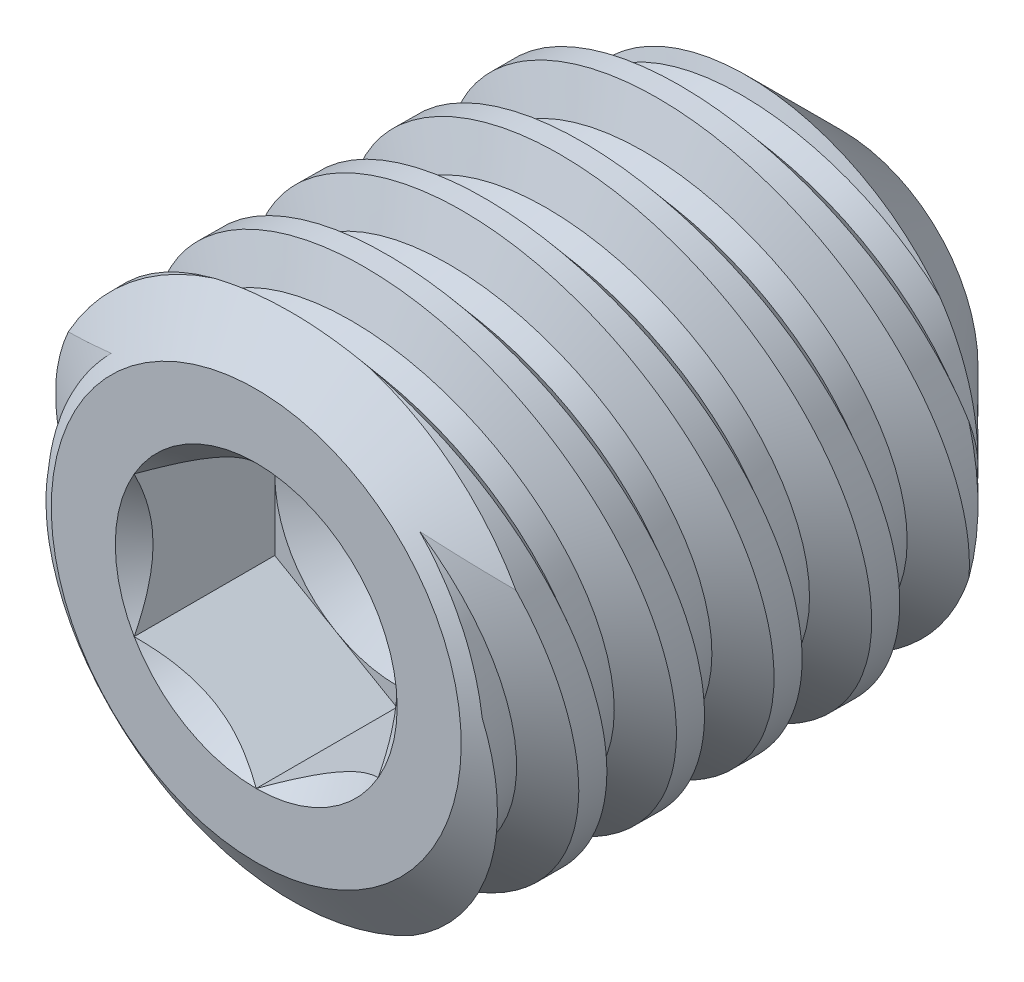
SolidWorks part; units mm, degrees
ref_plane "Front" through (0, 0, 0) normal (0, 0, 1) x (1, 0, 0)
ref_plane "Top" through (0, 0, 0) normal (0, 1, 0) x (1, 0, 0)
ref_plane "Right" through (0, 0, 0) normal (1, 0, 0) x (0, 0, -1)
sketch "Sketch22" plane through (0, 0, 0) normal (1, 0, 0) x (0, 0, -1)
  line L0 (-2.0493, 0) -> (-2.0493, 1.6662)
  line L1 (-2.0493, 1.6662) -> (-1.7576, 2.0828)
  line L2 (-1.7576, 2.0828) -> (1.7353, 2.0828)
  line L3 (1.7353, 2.0828) -> (2.7132, 1.1049)
  line L4 (2.7132, 1.1049) -> (2.0493, 0)
  line L5 (2.0493, 0) -> (-2.0493, 0)
  line L6 (2.0493, 0) -> (2.7132, 0) construction
  line L7 (2.7132, 0) -> (2.7132, 1.1049) construction
  line L8 (2.7132, -1.1049) -> (2.0493, 0) construction
  line L9 (-1.7576, -2.0828) -> (1.7353, -2.0828) construction
  dimension "Screw Dia" = 4.1656
  dimension "Length" = 4.7625
  dimension "D3" = 35
  dimension "Cup Point Dia" = 2.2098
  dimension "D5" = 118
  dimension "D6" = 45
  dimension "D7" = 3.3325
revolve "Revolve1" add sketch "Sketch22" angle 360 about L6
sketch "Sketch6" plane through (0, 0, 0) normal (1, 0, 0) x (0, 0, -1)
  line L0 (0.487, 2.0828) -> (1.2808, -2.0828) construction
  line L1 (-1.7576, 2.0828) -> (1.7353, 2.0828) construction
  line L2 (-1.7576, -2.0828) -> (1.7353, -2.0828) construction
  line L3 (0.487, 2.0828) -> (0.5845, 2.1014) construction
  line L4 (1.1035, 1.7629) -> (0.9086, 1.7258)
  line L5 (0.9086, 1.7258) -> (0.5845, 2.1014)
  line L6 (1.1035, 1.7629) -> (1.2667, 2.2314)
  line L7 (1.2667, 2.2314) -> (0.5845, 2.1014)
  line L8 (0.9415, 2.0828) -> (1.7353, -2.0828) construction
  line L9 (2.1898, 0.1622) -> (0.487, -0.1622) construction
  line L10 (0.9256, 2.1664) -> (1.006, 1.7443) construction
  line L13 (0.487, -2.0828) -> (0.487, 2.0828) construction
  line L14 (0.487, -2.0828) -> (1.2808, -2.0828) construction
  line L15 (1.2808, -2.0828) -> (1.7353, -2.0828) construction
  line L18 (0.487, 2.0828) -> (0.9415, 2.0828) construction
  point P18 (1.3384, 0)
  dimension "Pitch" = 0.7937
  dimension "D2" = 0.1984
  dimension "D3" = 60
  dimension "D1" = 0.7937
  dimension "D4" = 0.0992
revolve "Cut-Revolve8" cut sketch "Sketch6" angle 360 about L9
pattern_linear "LPattern1" count 5 spacing 0.7937 along (0, 0, 1) count 2 spacing 0.7937 along (0, 0, -1) of "Cut-Revolve8"
sketch "Sketch23" plane through (0, 0, 2.0493) normal (0, 0, 1) x (1, 0, 0)
  line L1 (0, 1.1457) -> (-0.9922, 0.5728)
  line L2 (-0.9922, 0.5728) -> (-0.9922, -0.5728)
  line L3 (-0.9922, -0.5728) -> (0, -1.1457)
  line L4 (0, -1.1457) -> (0.9922, -0.5728)
  line L5 (0.9922, -0.5728) -> (0.9922, 0.5728)
  line L6 (0.9922, 0.5728) -> (0, 1.1457)
  circle A0 centre (0, 0) radius 0.9922 construction
  dimension "Hex" = 1.9844
extrude "Cut-Extrude10" cut sketch "Sketch23" against normal blind 1.143
sketch "Sketch24" plane through (0, 0, 2.0493) normal (0, 0, 1) x (1, 0, 0)
  circle A0 centre (0, 0) radius 1.1457
extrude "Cut-Extrude11" cut sketch "Sketch24" against normal through all draft 45
sketch "Sketch26" plane through (0, 0, 0.9063) normal (0, 0, 1) x (1, 0, 0)
  circle A0 centre (0, 0) radius 0.9922 construction
  circle A1 centre (0, 0) radius 0.9922
extrude "Cut-Extrude12" cut sketch "Sketch26" against normal through all draft 59
equation "\"D2@Sketch6\"=\"Pitch@Sketch6\"/4"
equation "\"D4@Sketch6\"=\"Pitch@Sketch6\"/8"
equation "\"D1@Sketch6\"=\"Pitch@Sketch6\""
equation "\"D3@LPattern1\"=\"Pitch@Sketch6\""
equation "\"D1@LPattern1\"=(\"Length@Sketch22\"/\"Pitch@Sketch6\")-1"
equation "\"D4@LPattern1\"=\"Pitch@Sketch6\""
equation "\"D7@Sketch22\"=\"Screw Dia@Sketch22\"*.8"
